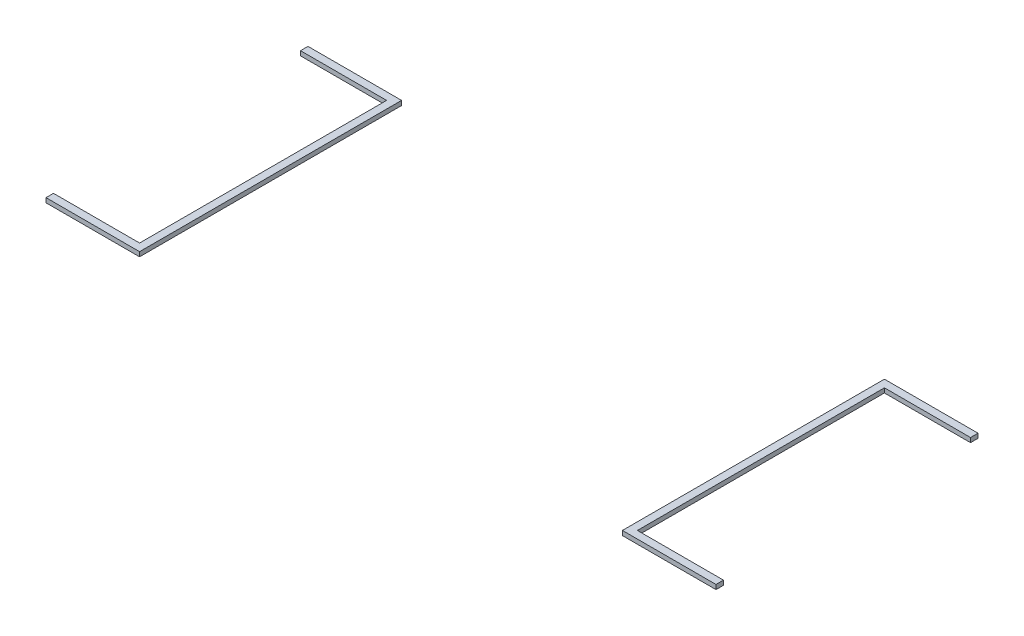
SolidWorks part; units mm, degrees
ref_plane "Спереди" through (0, 0, 0) normal (0, 0, 1) x (1, 0, 0)
ref_plane "Сверху" through (0, 0, 0) normal (0, 1, 0) x (1, 0, 0)
ref_plane "Справа" through (0, 0, 0) normal (1, 0, 0) x (0, 0, -1)
ref_plane "Плоскость4"
sketch "Эскиз1" plane through (0, 0, 0) normal (0, 1, 0) x (-1, 0, 0)
  line L0 (-645, -350) -> (-645, 350)
  line L1 (-645, 350) -> (-895, 350)
  line L2 (-895, 350) -> (-895, 330)
  line L3 (-895, 330) -> (-665, 330)
  line L4 (-665, 330) -> (-665, -330)
  line L5 (-665, -330) -> (-895, -330)
  line L6 (-895, -330) -> (-895, -350)
  line L7 (-895, -350) -> (-645, -350)
  line L8 (895, -350) -> (895, -330)
  line L9 (895, -330) -> (665, -330)
  line L10 (665, -330) -> (665, 330)
  line L11 (665, 330) -> (895, 330)
  line L12 (895, 330) -> (895, 350)
  line L13 (895, 350) -> (645, 350)
  line L14 (645, 350) -> (645, -350)
  line L15 (645, -350) -> (895, -350)
  dimension "D1" = 250
  dimension "D2" = 700
extrude "Выдавливание1" add sketch "Эскиз1" along normal blind 12 contours L6 L7 L0 L1 L2 L3 L4 L5 | L14 L15 L8 L9 L10 L11 L12 L13
